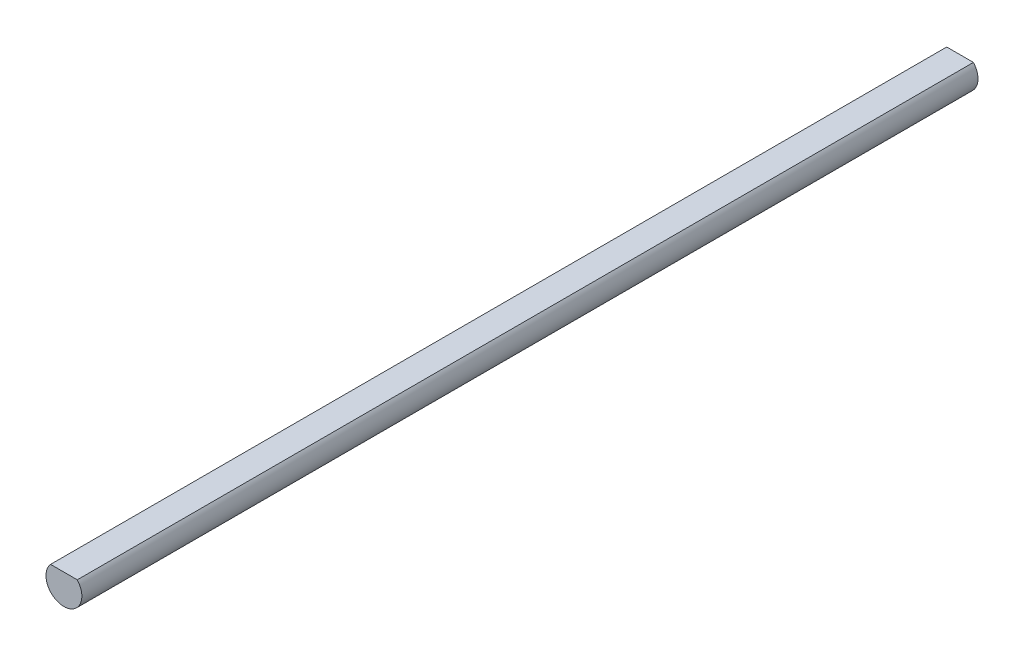
SolidWorks part; units mm, degrees
ref_plane "前视基准面" through (0, 0, 0) normal (0, 0, 1) x (1, 0, 0)
ref_plane "上视基准面" through (0, 0, 0) normal (0, 1, 0) x (1, 0, 0)
ref_plane "右视基准面" through (0, 0, 0) normal (1, 0, 0) x (0, 0, -1)
other "Configuration Table"
sketch "草图1" plane through (0, 0, 0) normal (0, 0, 1) x (1, 0, 0)
  circle A0 centre (0, 0) radius 6
  dimension "D1" = 12
extrude "凸台-拉伸1" add sketch "草图1" along normal blind 300
sketch "草图2" plane through (0, 0, 300) normal (0, 0, 1) x (1, 0, 0)
  line L0 (-4.4721, 4) -> (4.4721, 4)
  arc A0 (4.4721, 4) -> (-4.4721, 4) centre (0, 0) ccw
  dimension "D1" = 12
  dimension "D2" = 4
extrude "切除-拉伸1" cut sketch "草图2" against normal through all
